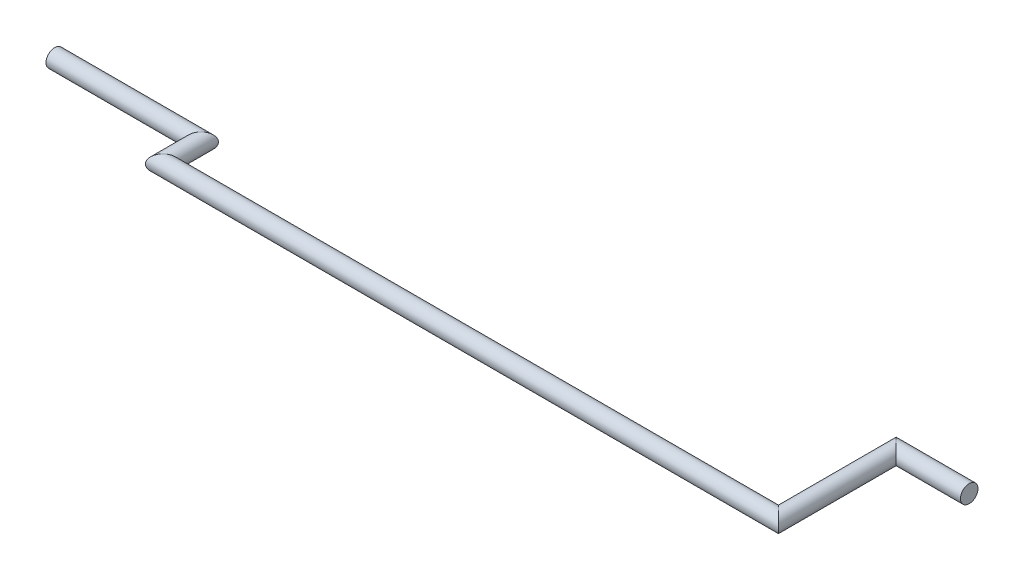
SolidWorks part; units mm, degrees
ref_plane "Front Plane" through (0, 0, 0) normal (0, 0, 1) x (1, 0, 0)
ref_plane "Top Plane" through (0, 0, 0) normal (0, 1, 0) x (1, 0, 0)
ref_plane "Right Plane" through (0, 0, 0) normal (1, 0, 0) x (0, 0, -1)
sketch "Sketch1" plane through (0, 0, 0) normal (0, 1, 0) x (1, 0, 0)
  line L0 (0, 0) -> (0, 2.6)
  line L1 (0, 2.6) -> (-10, 2.6)
  line L2 (0, 0) -> (42.11, 0)
  line L3 (42.11, 0) -> (42.11, 8.05)
  line L4 (42.11, 8.05) -> (47.11, 8.05)
  dimension "D1" = 42.11
  dimension "D2" = 2.6
  dimension "D3" = 10
  dimension "D4" = 5
  dimension "D5" = 8.05
sweep "Sweep1" add path "Sketch1" circular profile diameter 1.2 parameters "D3"=1.2
